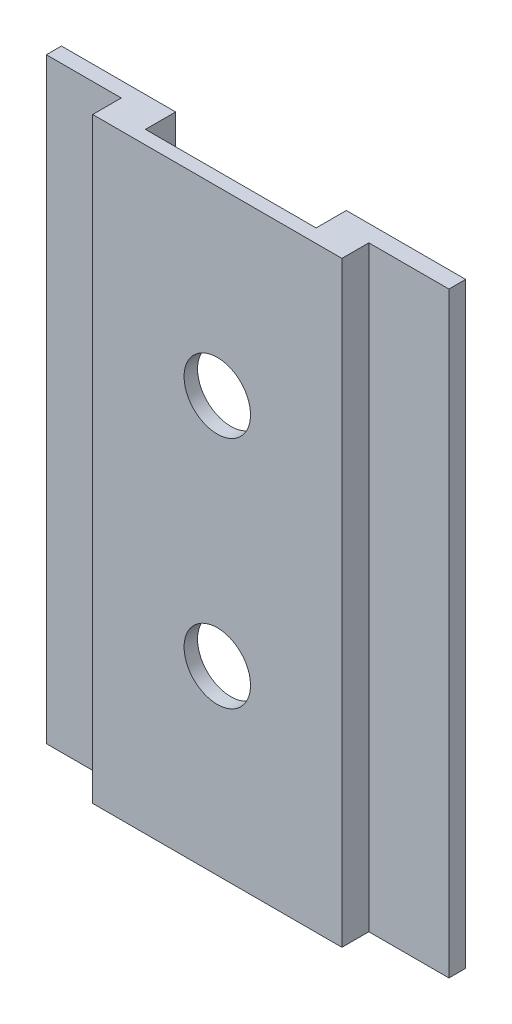
SolidWorks part; units mm, degrees
ref_plane "Front Plane" through (0, 0, 0) normal (0, 0, 1) x (1, 0, 0)
ref_plane "Top Plane" through (0, 0, 0) normal (0, 1, 0) x (1, 0, 0)
ref_plane "Right Plane" through (0, 0, 0) normal (1, 0, 0) x (0, 0, -1)
sketch "Sketch1" plane through (0, 0, 0) normal (0, 1, 0) x (1, 0, 0)
  line L0 (0, 0) -> (20.955, 0)
  line L1 (20.955, 0) -> (20.955, 2.2658)
  line L2 (20.955, 2.2658) -> (27.686, 2.2658)
  line L3 (27.686, 2.2658) -> (27.686, 3.6735)
  line L4 (27.686, 3.6735) -> (17.653, 3.6735)
  line L5 (17.653, 3.6735) -> (17.653, 1.1329)
  line L6 (17.653, 1.1329) -> (3.302, 1.1329)
  line L7 (3.302, 1.1329) -> (3.302, 3.6735)
  line L8 (3.302, 3.6735) -> (-6.2992, 3.6735)
  line L9 (-6.2992, 3.6735) -> (-6.2992, 2.4032)
  line L10 (-6.2992, 2.4032) -> (0, 2.4032)
  line L11 (0, 2.4032) -> (0, 0)
  dimension "D1" = 33.9852
  dimension "D2" = 14.351
  dimension "D3" = 3.302
  dimension "D4" = 3.302
  dimension "D5" = 9.6012
extrude "Boss-Extrude1" add sketch "Sketch1" along normal blind 50.165
sketch "Sketch2" plane through (0, 0, -1.1329) normal (0, 0, -1) x (-1, 0, 0)
  line L0 (-17.653, 50.165) -> (-3.302, 50.165) construction
  line L1 (-3.302, 25.0825) -> (-17.653, 25.0825) construction
  line L2 (-3.302, 50.165) -> (-3.302, 0) construction
  line L3 (-17.653, 50.165) -> (-17.653, 0) construction
  circle A0 centre (-10.4775, 34.925) radius 2.794
  circle A1 centre (-10.4775, 15.24) radius 2.794
  point P2 (-10.4775, 50.165)
  dimension "D1" = 15.24
extrude "Cut-Extrude1" cut sketch "Sketch2" against normal blind 50.165
